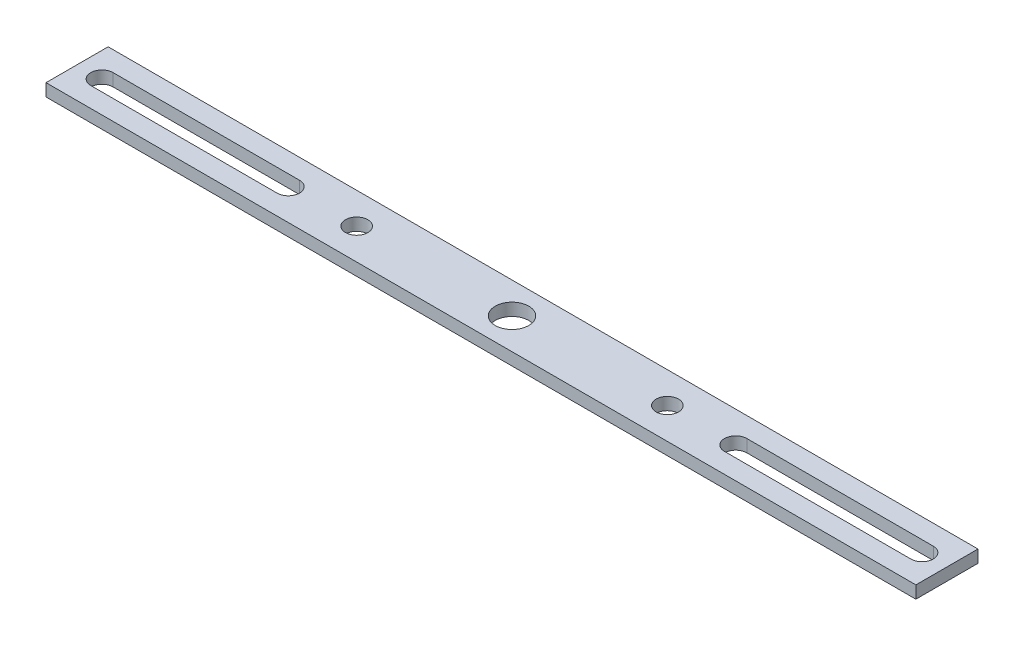
SolidWorks part; units mm, degrees
material "AISI 304"
ref_plane "Front Plane" through (0, 0, 0) normal (0, 0, 1) x (1, 0, 0)
ref_plane "Top Plane" through (0, 0, 0) normal (0, 1, 0) x (1, 0, 0)
ref_plane "Right Plane" through (0, 0, 0) normal (1, 0, 0) x (0, 0, -1)
sketch "Sketch1" plane through (0, 0, 0) normal (0, 1, 0) x (1, 0, 0)
  line L0 (-83.82, 0) -> (-45.72, 0) construction
  line L1 (-88.9, 6.35) -> (88.9, 6.35)
  line L2 (-88.9, 6.35) -> (-88.9, -6.35)
  line L3 (-88.9, -6.35) -> (88.9, -6.35)
  line L4 (88.9, 6.35) -> (88.9, -6.35)
  line L5 (-88.9, 6.35) -> (88.9, -6.35) construction
  line L6 (-88.9, -6.35) -> (88.9, 6.35) construction
  line L7 (-83.82, 2.286) -> (-45.72, 2.286)
  line L8 (-83.82, -2.286) -> (-45.72, -2.286)
  line L9 (83.82, 0) -> (45.72, 0) construction
  line L10 (83.82, -2.286) -> (45.72, -2.286)
  line L11 (83.82, 2.286) -> (45.72, 2.286)
  circle A0 centre (0, 0) radius 3.429
  arc A1 (-83.82, 2.286) -> (-83.82, -2.286) centre (-83.82, 0) ccw
  arc A2 (-45.72, -2.286) -> (-45.72, 2.286) centre (-45.72, 0) ccw
  arc A3 (83.82, -2.286) -> (83.82, 2.286) centre (83.82, 0) ccw
  arc A4 (45.72, 2.286) -> (45.72, -2.286) centre (45.72, 0) ccw
  circle A5 centre (-31.75, 0) radius 2.286
  circle A6 centre (31.75, 0) radius 2.286
  point P0 (0, 0)
  point P10 (-64.77, 0)
  point P15 (64.77, 0)
  dimension "D3" = 6.858
  dimension "D4" = 2.286
  dimension "D5" = 2.286
  dimension "D6" = 4.572
  dimension "D7" = 4.572
  dimension "D10" = 5.08
  dimension "D1" = 12.7
  dimension "D2" = 177.8
  dimension "D8" = 31.75
  dimension "D9" = 31.75
  dimension "D11" = 5.08
  dimension "D12" = 38.1
  dimension "D13" = 38.1
  dimension "D14" = 6.35
  dimension "D15" = 6.35
extrude "Boss-Extrude1" add sketch "Sketch1" along normal blind 2.54
